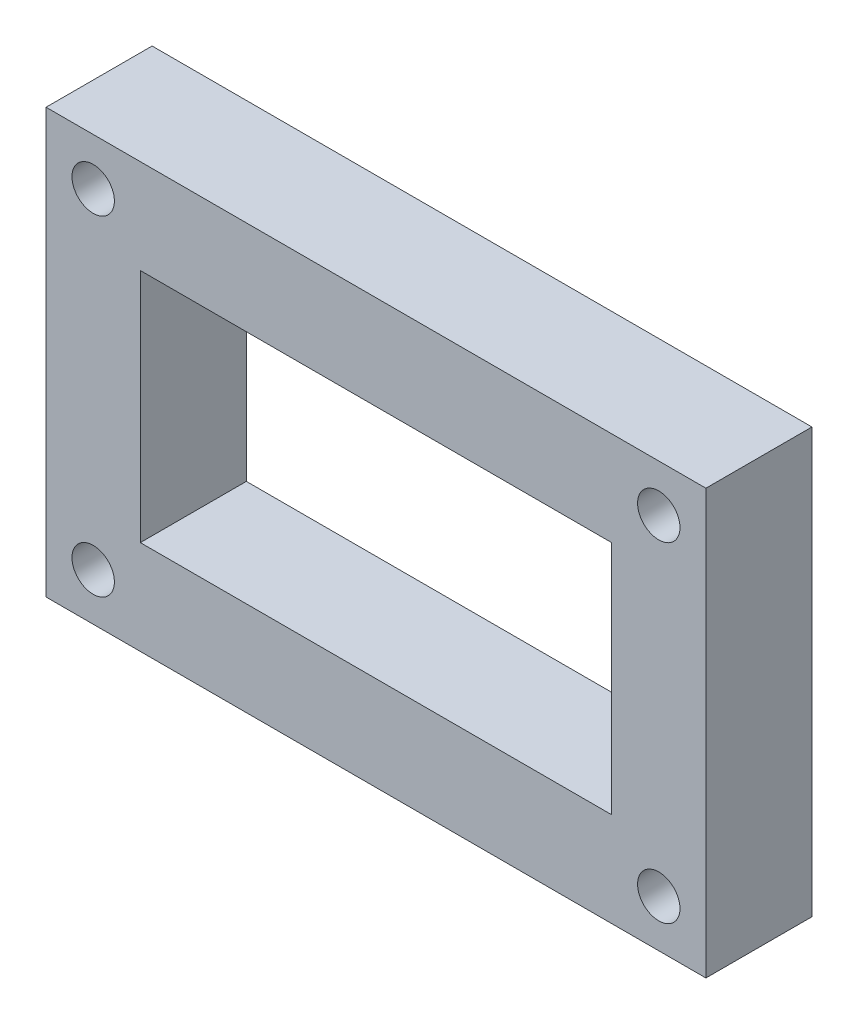
SolidWorks part; units mm, degrees
ref_plane "Front Plane" through (0, 0, 0) normal (0, 0, 1) x (1, 0, 0)
ref_plane "Top Plane" through (0, 0, 0) normal (0, 1, 0) x (1, 0, 0)
ref_plane "Right Plane" through (0, 0, 0) normal (1, 0, 0) x (0, 0, -1)
sketch "Sketch1" plane through (0, 0, 0) normal (0, 0, 1) x (1, 0, 0)
  line L1 (-25.4, 12.7) -> (25.4, 12.7)
  line L2 (-25.4, 12.7) -> (-25.4, -12.7)
  line L3 (-25.4, -12.7) -> (25.4, -12.7)
  line L4 (25.4, 12.7) -> (25.4, -12.7)
  line L5 (-25.4, 12.7) -> (25.4, -12.7) construction
  line L6 (-25.4, -12.7) -> (25.4, 12.7) construction
  line L7 (-35.56, 22.86) -> (35.56, 22.86)
  line L8 (-35.56, 22.86) -> (-35.56, -22.86)
  line L9 (-35.56, -22.86) -> (35.56, -22.86)
  line L10 (35.56, 22.86) -> (35.56, -22.86)
  line L11 (-35.56, 22.86) -> (35.56, -22.86) construction
  line L12 (-35.56, -22.86) -> (35.56, 22.86) construction
  line L13 (-30.48, 17.78) -> (30.48, 17.78) construction
  line L14 (-30.48, 17.78) -> (-30.48, -17.78) construction
  line L15 (-30.48, -17.78) -> (30.48, -17.78) construction
  line L16 (30.48, 17.78) -> (30.48, -17.78) construction
  line L17 (-30.48, 17.78) -> (30.48, -17.78) construction
  line L18 (-30.48, -17.78) -> (30.48, 17.78) construction
  circle A0 centre (-30.48, 17.78) radius 2.286
  circle A1 centre (-30.48, -17.78) radius 2.286
  circle A2 centre (30.48, -17.78) radius 2.286
  circle A3 centre (30.48, 17.78) radius 2.286
  point P0 (0, 0)
  point P6 (0, 0)
  point P11 (0, 0)
  dimension "D7" = 4.572
  dimension "D1" = 50.8
  dimension "D2" = 25.4
  dimension "D3" = 10.16
  dimension "D4" = 10.16
  dimension "D5" = 5.08
  dimension "D6" = 5.08
extrude "Boss-Extrude1" add sketch "Sketch1" along normal blind 11.43
